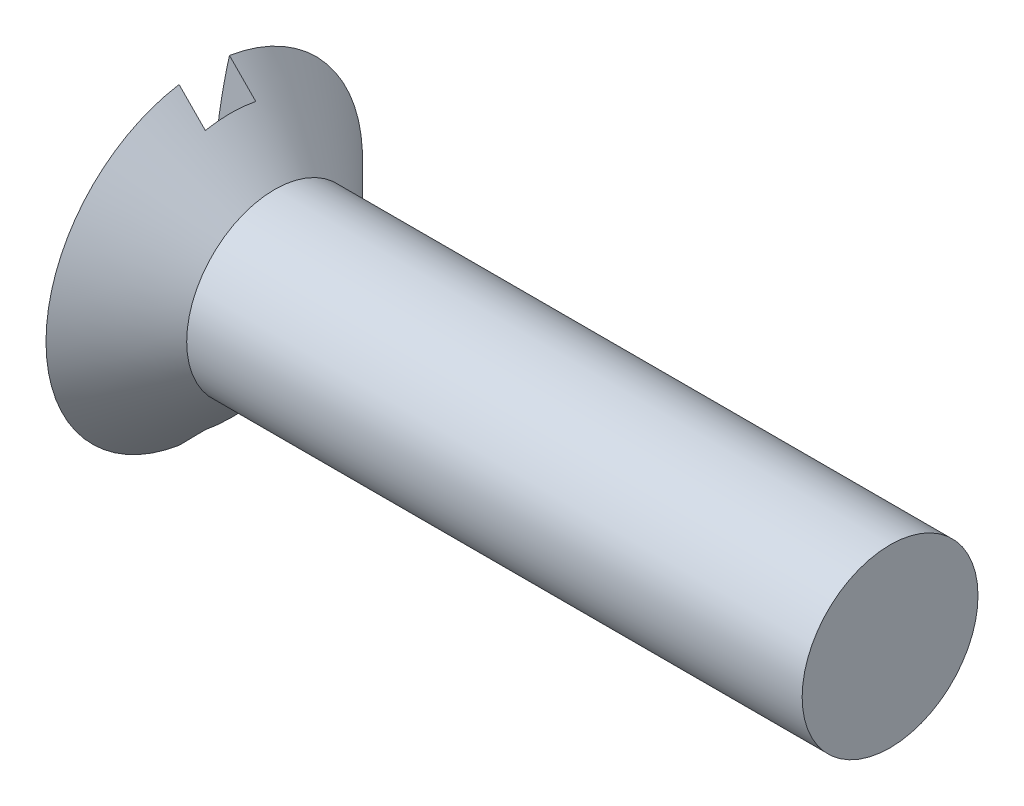
SolidWorks part; units mm, degrees
ref_plane "Front Plane" through (0, 0, 0) normal (0, 0, 1) x (1, 0, 0)
ref_plane "Top Plane" through (0, 0, 0) normal (0, 1, 0) x (1, 0, 0)
ref_plane "Right Plane" through (0, 0, 0) normal (1, 0, 0) x (0, 0, -1)
sketch "Sketch1" plane through (0, 0, 0) normal (0, 0, 1) x (1, 0, 0)
  line L0 (0, 0) -> (12.7, 0)
  line L1 (12.7, 0) -> (12.7, 1.5875)
  line L2 (12.7, 1.5875) -> (1.5875, 1.5875)
  line L3 (1.5875, 1.5875) -> (0.3175, 2.8575)
  line L4 (0, 0) -> (0, -3.5825) construction
  arc A0 (0.3175, 2.8575) -> (0, 0) centre (13.0175, 0) ccw
  dimension "D1" = 2.8575
  dimension "D2" = 1.5875
  dimension "D3" = 12.7
  dimension "D4" = 45
  dimension "D5" = 1.5875
revolve "Revolve1" add sketch "Sketch1" angle 360 about L0
sketch "Sketch2" plane through (0, 0, 0) normal (0, 1, 0) x (1, 0, 0)
  line L1 (-0.792, 0.4546) -> (0.792, 0.4546)
  line L2 (-0.792, 0.4546) -> (-0.792, -0.4546)
  line L3 (-0.792, -0.4546) -> (0.792, -0.4546)
  line L4 (0.792, 0.4546) -> (0.792, -0.4546)
  line L5 (-0.792, 0.4546) -> (0.792, -0.4546) construction
  line L6 (-0.792, -0.4546) -> (0.792, 0.4546) construction
  point P0 (0, 0)
extrude "Cut-Extrude1" cut sketch "Sketch2" against normal mid plane 8.128
